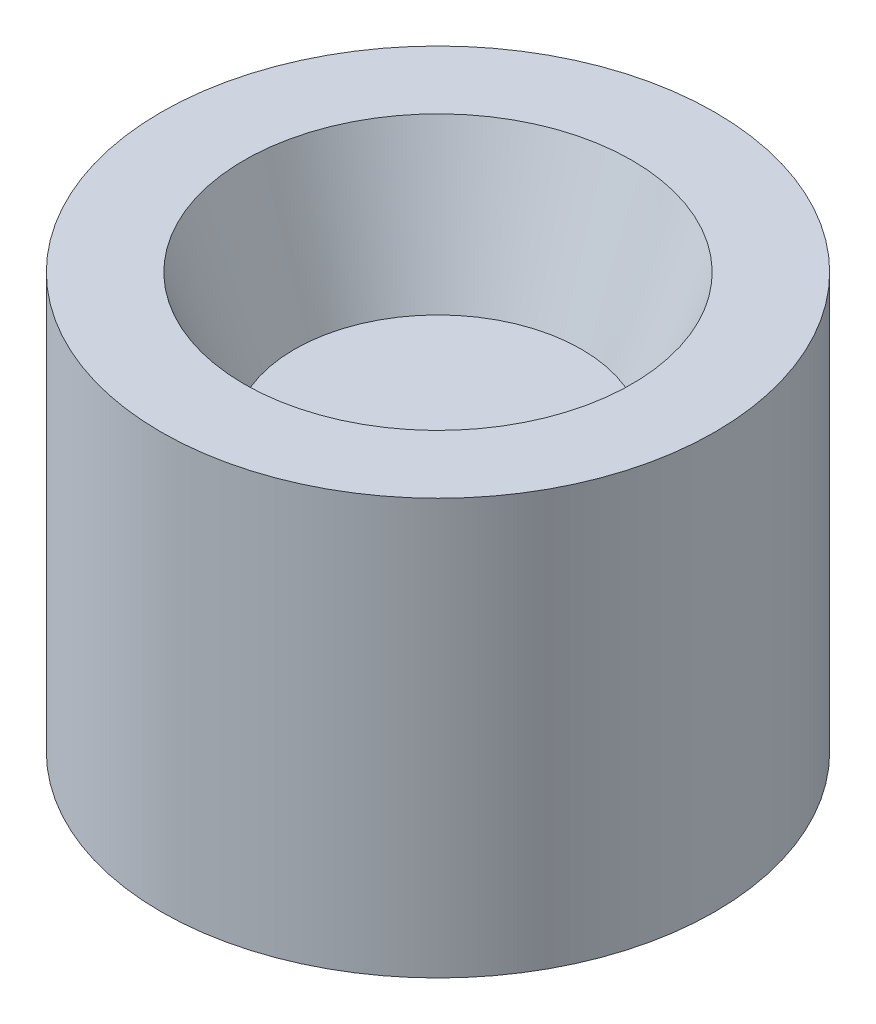
SolidWorks part; units mm, degrees
ref_plane "Front Plane" through (0, 0, 0) normal (0, 0, 1) x (1, 0, 0)
ref_plane "Top Plane" through (0, 0, 0) normal (0, 1, 0) x (1, 0, 0)
ref_plane "Right Plane" through (0, 0, 0) normal (1, 0, 0) x (0, 0, -1)
sketch "Sketch1" plane through (0, 0, 0) normal (0, 0, 1) x (1, 0, 0)
  line L0 (0, 0) -> (0, 6.35)
  line L1 (0, 6.35) -> (6.5788, 6.35)
  line L2 (6.5788, 6.35) -> (8.89, 12.7)
  line L3 (8.89, 12.7) -> (12.7, 12.7)
  line L4 (12.7, 12.7) -> (12.7, -6.35)
  line L5 (12.7, -6.35) -> (8.89, -6.35)
  line L6 (8.89, -6.35) -> (6.5788, 0)
  line L7 (6.5788, 0) -> (0, 0)
  dimension "D1" = 19.05
  dimension "D2" = 3.81
  dimension "D3" = 3.81
  dimension "D4" = 6.35
  dimension "D5" = 110
  dimension "D6" = 110
  dimension "D7" = 12.7
  dimension "D8" = 6.35
revolve "Revolve1" add sketch "Sketch1" angle 360 about L0
